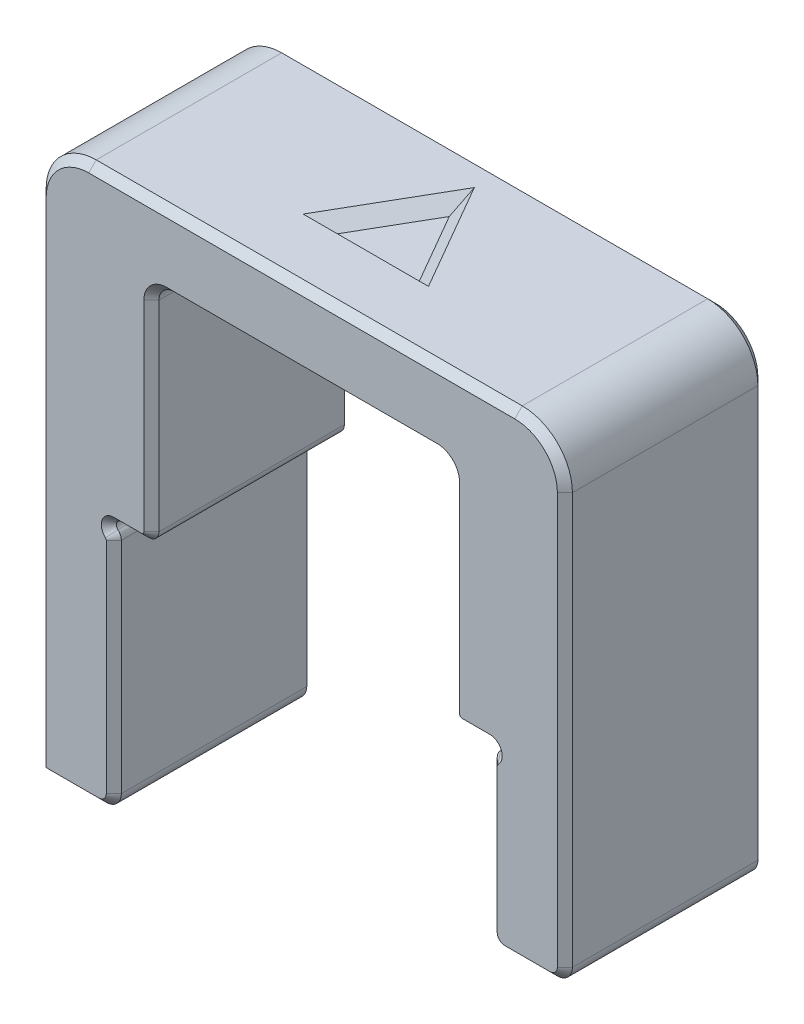
SolidWorks part; units mm, degrees
ref_plane "Front Plane" through (0, 0, 0) normal (0, 0, 1) x (1, 0, 0)
ref_plane "Top Plane" through (0, 0, 0) normal (0, 1, 0) x (1, 0, 0)
ref_plane "Right Plane" through (0, 0, 0) normal (1, 0, 0) x (0, 0, -1)
sketch "Sketch1" plane through (0, 0, 0) normal (0, 0, 1) x (1, 0, 0)
  line L0 (0, 9) -> (6, 9)
  line L1 (6, 9) -> (6, 0)
  line L2 (6, 0) -> (7.5, 0)
  line L3 (7.5, 0) -> (7.5, -7)
  line L4 (7.5, -7) -> (10.5, -7)
  line L5 (10.5, -7) -> (10.5, 12)
  line L6 (10.5, 12) -> (0, 12)
  line L7 (0, 12) -> (0, 9)
  line L8 (0, 0) -> (0, 23.8381) construction
  dimension "D1" = 9
  dimension "D2" = 12
  dimension "D3" = 7
  dimension "D4" = 15
  dimension "D5" = 3
  dimension "D6" = 3
extrude "Boss-Extrude1" add sketch "Sketch1" along normal mid plane 8
sketch "Sketch2" plane through (0, 0, 4) normal (0, 0, 1) x (1, 0, 0)
  line L0 (7.5, 0) -> (7.5, -7) construction
  circle A0 centre (7.5, -0.2) radius 0.2
  dimension "D1" = 0.4
extrude "Cut-Extrude1" cut sketch "Sketch2" against normal up to surface (8 mm away) up to face at (6, 3.5, -4)
fillet "Fillet2" radius 0.4 2 edges at (7.5, -0.4, 0) (6, 0, 0)
fillet "Fillet1" radius 0.6 3 edges at (7.5, -7, 0) (6, 9, 0) (10.5, -7, 0)
fillet "Fillet3" radius 2 1 edges at (10.5, 12, 0)
mirror "Mirror1" about plane through (0, 12, 4) normal (1, 0, 0) of bodies 102
sketch "Sketch3" plane through (0, 0, 4) normal (0, 0, 1) x (1, 0, 0)
  line L0 (-8.1, -7) -> (-9.9, -7) construction
  line L1 (-8.1, -7) -> (-9.9, -7)
  line L2 (-10.5, -6.4) -> (-10.5, -10)
  line L3 (-10.5, -10) -> (-7.5, -10)
  line L4 (-7.5, -10) -> (-7.5, -6.4)
  arc A0 (-8.1, -7) -> (-7.5, -6.4) centre (-8.1, -6.4) ccw construction
  arc A1 (-10.5, -6.4) -> (-9.9, -7) centre (-9.9, -6.4) ccw construction
  arc A2 (-8.1, -7) -> (-7.5, -6.4) centre (-8.1, -6.4) ccw
  arc A3 (-10.5, -6.4) -> (-9.9, -7) centre (-9.9, -6.4) ccw
  dimension "D1" = 3
extrude "Boss-Extrude2" add sketch "Sketch3" against normal up to surface (8 mm away) up to face at (0, 0.9439, -4)
fillet "Fillet4" radius 0.6 1 edges at (-7.5, -10, 0)
sketch "Sketch4" plane through (0, 12, 0) normal (0, 1, 0) x (1, 0, 0)
  line L0 (-2.5, -1.4434) -> (2.5, -1.4434)
  line L1 (2.5, -1.4434) -> (0, 2.8868)
  line L2 (0, 2.8868) -> (-2.5, -1.4434)
  line L3 (2.5, -1.4434) -> (-1.25, 0.7217) construction
  line L4 (-2.5, -1.4434) -> (1.25, 0.7217) construction
  dimension "D1" = 5
extrude "Cut-Extrude2" cut sketch "Sketch4" against normal blind 0.5 draft 45
chamfer "Chamfer1" distance 0.3 angle 45 50 edges at (-9.3, -10, 4) (0, 9, -4) (-9.3, -10, -4) (-7.6757, -9.8243, 4) (-7.6757, -9.8243, -4) (6.95, 0, -4) (6.95, 0, 4) (7.5, -3.5236, -4) (7.6868, -0.1286, -4) (7.5349, -0.4839, -4) (6.1172, 0.1172, -4) (7.6868, -0.1286, 4) (7.5, -3.5236, 4) (7.5349, -0.4839, 4) (6.1172, 0.1172, 4) (10.5, 1.8, -4) (10.5, 1.8, 4) (6, 4.4, -4) (9, -7, -4) (7.6757, -6.8243, -4) (10.3243, -6.8243, -4) (9, -7, 4) (6, 4.4, 4) (7.6757, -6.8243, 4) (10.3243, -6.8243, 4) (5.8243, 8.8243, -4) (5.8243, 8.8243, 4) (0, 12, -4) (0, 12, 4) (9.9142, 11.4142, -4) (9.9142, 11.4142, 4) (-6, 4.4, 4) (-6.95, 0, 4) (-7.5, -5.0236, 4) (-10.5, 0, 4) (-7.6868, -0.1286, 4) (-6, 4.4, -4) (-6.95, 0, -4) (-7.5, -5.0236, -4) (-10.5, 0, -4) (-7.6868, -0.1286, -4) (-6.1172, 0.1172, 4) (-6.1172, 0.1172, -4) (-7.5349, -0.4839, 4) (-7.5349, -0.4839, -4) (-5.8243, 8.8243, 4) (-5.8243, 8.8243, -4) (-9.9142, 11.4142, 4) (-9.9142, 11.4142, -4) (0, 9, 4)
equation "\"D1@Fillet4\"=\"D1@Fillet1\""
